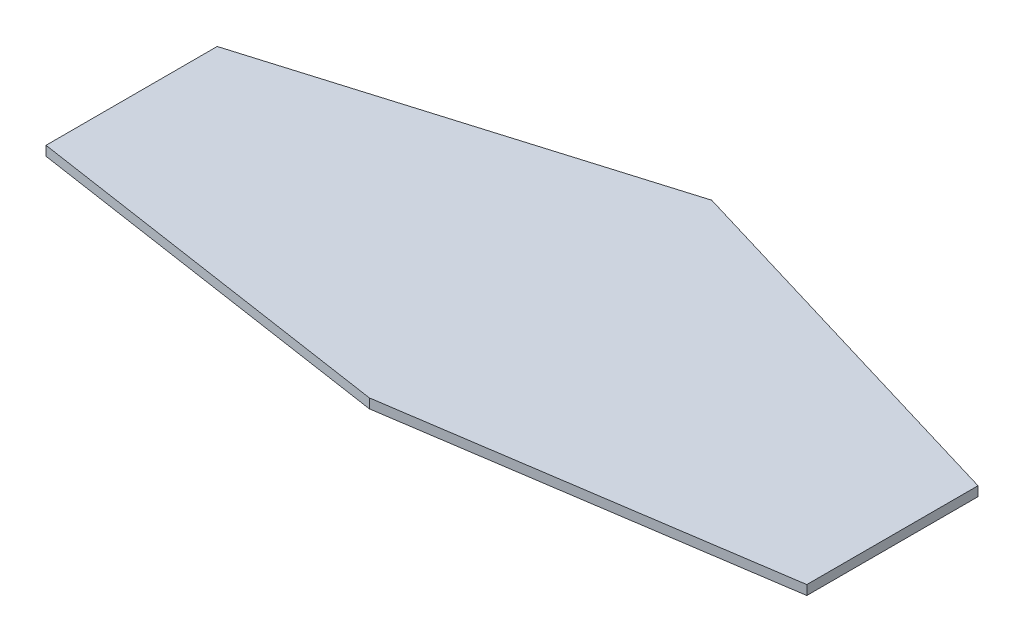
SolidWorks part; units mm, degrees
ref_plane "前视基准面" through (0, 0, 0) normal (0, 0, 1) x (1, 0, 0)
ref_plane "上视基准面" through (0, 0, 0) normal (0, 1, 0) x (1, 0, 0)
ref_plane "右视基准面" through (0, 0, 0) normal (1, 0, 0) x (0, 0, -1)
sketch "草图1" plane through (0, 0, 0) normal (0, 1, 0) x (1, 0, 0)
  line L0 (0, 120) -> (-200, 60)
  line L1 (-200, 60) -> (-200, -30)
  line L2 (-200, -30) -> (0, -60)
  line L3 (0, -60) -> (200, -30)
  line L4 (200, -30) -> (200, 60)
  line L5 (200, 60) -> (0, 120)
  dimension "D1" = 120
  dimension "D2" = 180
  dimension "D3" = 200
  dimension "D4" = 200
  dimension "D5" = 90
  dimension "D6" = 60
extrude "拉伸1" add sketch "草图1" along normal blind 5
